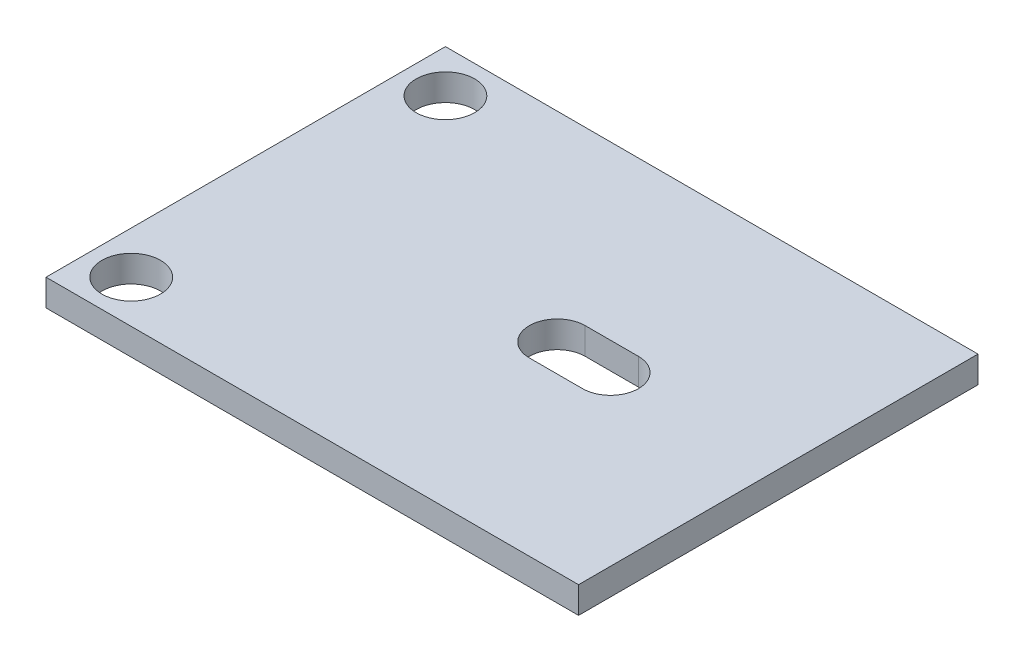
SolidWorks part; units mm, degrees
ref_plane "Plan de face" through (0, 0, 0) normal (0, 0, 1) x (1, 0, 0)
ref_plane "Plan de dessus" through (0, 0, 0) normal (0, 1, 0) x (1, 0, 0)
ref_plane "Plan de droite" through (0, 0, 0) normal (1, 0, 0) x (0, 0, -1)
sketch "Esquisse1" plane through (0, 0, 0) normal (0, 1, 0) x (1, 0, 0)
  line L1 (0, -7.5) -> (20, -7.5)
  line L2 (0, -7.5) -> (0, 7.5)
  line L3 (0, 7.5) -> (20, 7.5)
  line L4 (20, -7.5) -> (20, 7.5)
  dimension "D1" = 20
  dimension "D2" = 15
extrude "Boss.-Extru.1" add sketch "Esquisse1" along normal blind 1
sketch "Esquisse2" plane through (0, 1, 0) normal (0, 1, 0) x (1, 0, 0)
  line L0 (11.7, 0) -> (13.7, 0) construction
  line L1 (11.7, 1.05) -> (13.7, 1.05)
  line L2 (11.7, -1.05) -> (13.7, -1.05)
  line L3 (0, 7.5) -> (0, -7.5) construction
  line L4 (20, 7.5) -> (0, 7.5) construction
  line L5 (0, -7.5) -> (20, -7.5) construction
  line L6 (20, -7.5) -> (20, 7.5) construction
  arc A0 (11.7, 1.05) -> (11.7, -1.05) centre (11.7, 0) ccw
  arc A1 (13.7, -1.05) -> (13.7, 1.05) centre (13.7, 0) ccw
  circle A2 centre (1.6, 5.9) radius 1.1
  circle A3 centre (1.6, -5.9) radius 1.1
  point P3 (12.7, 0)
  dimension "D1" = 2.2
  dimension "D6" = 1.05
  dimension "D2" = 1.6
  dimension "D3" = 1.6
  dimension "D4" = 1.6
  dimension "D5" = 1.6
  dimension "D7" = 2
  dimension "D8" = 7.3
extrude "Enlèv. mat.-Extru.1" cut sketch "Esquisse2" against normal through all
